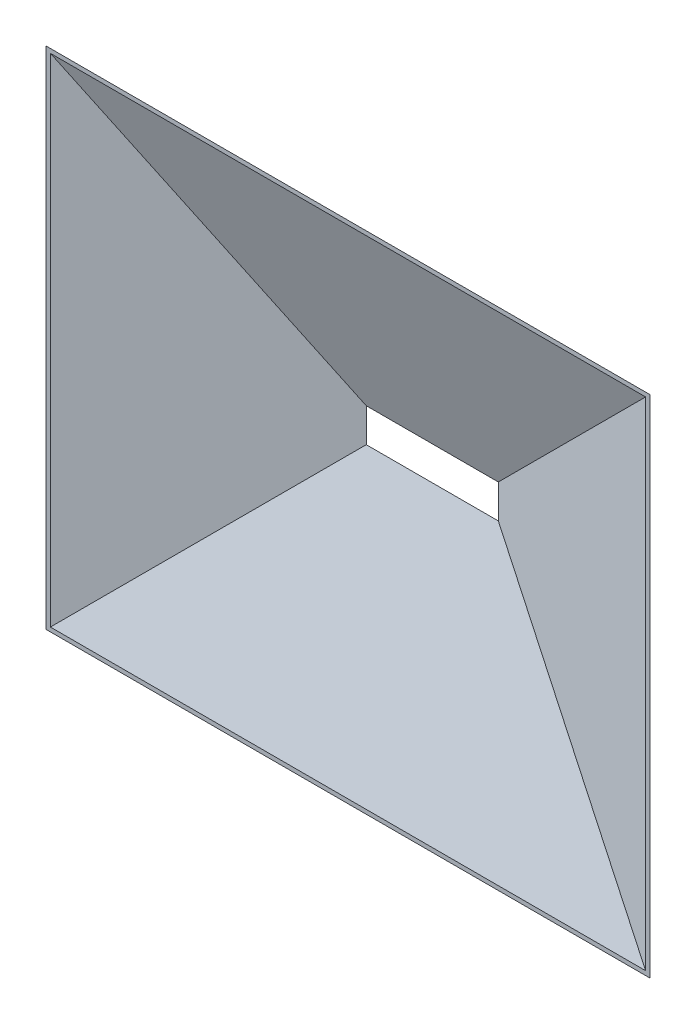
SolidWorks part; units mm, degrees
ref_plane "Alzado" through (0, 0, 0) normal (0, 0, 1) x (1, 0, 0)
ref_plane "Planta" through (0, 0, 0) normal (0, 1, 0) x (1, 0, 0)
ref_plane "Vista lateral" through (0, 0, 0) normal (1, 0, 0) x (0, 0, -1)
sketch "Croquis1" plane through (0, 0, 0) normal (0, 0, 1) x (1, 0, 0)
  line L1 (-50, -15) -> (50, -15)
  line L2 (-50, -15) -> (-50, 15)
  line L3 (-50, 15) -> (50, 15)
  line L4 (50, -15) -> (50, 15)
  line L5 (-50, -15) -> (50, 15) construction
  line L6 (-50, 15) -> (50, -15) construction
  point P0 (0, 0)
  dimension "D1" = 100
  dimension "D2" = 30
extrude "Saliente-Extruir1" add sketch "Croquis1" along normal blind 60 draft 70
sketch "Croquis2" plane through (0, 0, 0) normal (0, 0, -1) x (-1, 0, 0)
  line L4 (-50, 15) -> (-50, -15)
  line L5 (-50, -15) -> (50, -15)
  line L6 (50, -15) -> (50, 15)
  line L7 (50, 15) -> (-50, 15)
  line L8 (-50, 15) -> (-50, -15)
  line L9 (-50, -15) -> (50, -15)
  line L10 (50, -15) -> (50, 15)
  line L11 (50, 15) -> (-50, 15)
  line L16 (-47, 12) -> (-47, -12)
  line L17 (-47, -12) -> (47, -12)
  line L18 (47, -12) -> (47, 12)
  line L19 (47, 12) -> (-47, 12)
  line L20 (-47, 12) -> (-47, -12)
  line L21 (-47, -12) -> (47, -12)
  line L22 (47, -12) -> (47, 12)
  line L23 (47, 12) -> (-47, 12)
  dimension "D1" = 0
  dimension "D2" = 3
extrude "Cortar-Extruir1" cut sketch "Croquis2" against normal blind 60 draft 70 contours L22 L23 L20 L21
